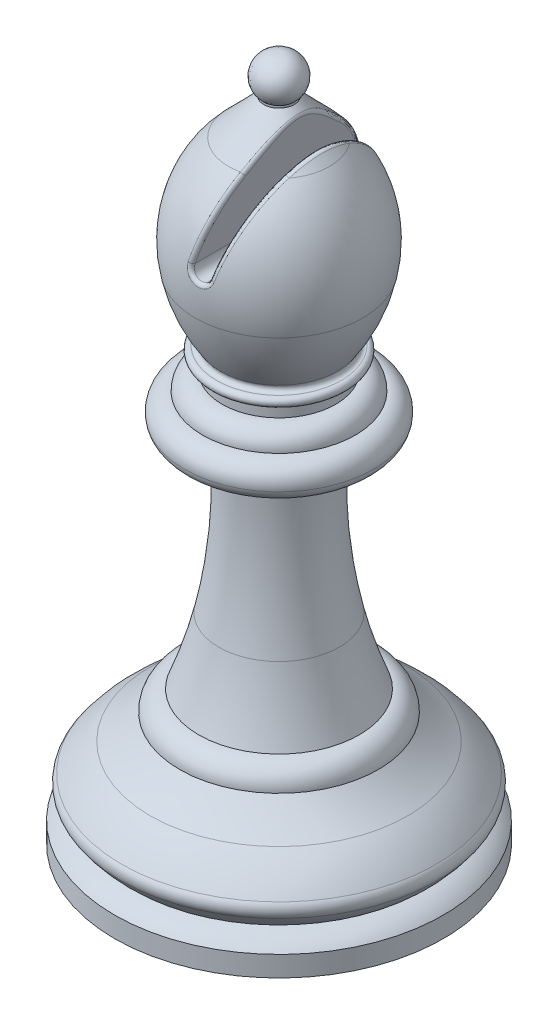
SolidWorks part; units mm, degrees
material "CA"
ref_plane "Front Plane" through (0, 0, 0) normal (0, 0, 1) x (1, 0, 0)
ref_plane "Top Plane" through (0, 0, 0) normal (0, 1, 0) x (1, 0, 0)
ref_plane "Right Plane" through (0, 0, 0) normal (1, 0, 0) x (0, 0, -1)
sketch "Sketch1" plane through (0, 0, 0) normal (0, 0, 1) x (1, 0, 0)
  line L0 (15.3, 173.706) -> (127.3, 173.706) construction
  line L1 (0, 0) -> (-11.9047, 0)
  line L2 (-11.9047, 0) -> (-11.9047, 1.4795)
  line L3 (-3.6158, 26.0106) -> (-5.794, 26.0106)
  line L4 (-4.1156, 29.6179) -> (-4.1156, 30.5678)
  line L5 (-3.6528, 44.2984) -> (-1.1, 46.9038)
  line L6 (-1.1, 46.9038) -> (-1.1, 47.0622)
  line L7 (0, 49.5976) -> (0, 0)
  arc A0 (-11.9047, 1.4795) -> (-10.4944, 2.3281) centre (-9.7951, -0.4301) cw
  arc A1 (-11.4556, 3.4168) -> (-10.4944, 2.3281) centre (-6.3809, 6.9286) ccw
  arc A2 (-11.4556, 3.4168) -> (-11.3893, 4.4063) centre (-10.8009, 3.8699) cw
  arc A3 (-11.3893, 4.4063) -> (-9.3337, 6.424) centre (-4.2404, -0.821) cw
  arc A4 (-9.3337, 6.424) -> (-7.1897, 8.2451) centre (-18.1976, 19.0323) ccw
  arc A5 (-7.1897, 8.2451) -> (-5.8113, 9.7342) centre (-5.7284, 8.275) cw
  arc A6 (-5.8113, 9.7342) -> (-4.3585, 14.505) centre (-36.4302, 21.6652) ccw
  arc A7 (-4.3585, 14.505) -> (-3.6158, 26.0106) centre (-40.757, 22.6312) ccw
  arc A8 (-5.794, 26.0106) -> (-6.8316, 26.8951) centre (-5.794, 27.0615) cw
  arc A9 (-6.8316, 26.8951) -> (-5.5288, 28.386) centre (-5.5604, 27.099) cw
  arc A10 (-5.5288, 28.386) -> (-4.1156, 29.6179) centre (-4.2879, 28.3889) cw
  arc A11 (-4.1156, 30.5678) -> (-4.61, 30.6582) centre (-3.5644, 34.9779) cw
  arc A12 (-4.61, 30.6582) -> (-4.5118, 31.3088) centre (-4.5323, 30.9792) cw
  arc A13 (-4.5118, 31.3088) -> (-4.2557, 31.7587) centre (-4.4939, 31.5964) ccw
  arc A14 (-4.2557, 31.7587) -> (-6.0674, 36.0018) centre (5.5937, 38.4723) cw
  arc A15 (-6.0674, 36.0018) -> (-3.6528, 44.2984) centre (2.8803, 37.8974) cw
  arc A16 (-1.1, 47.0622) -> (0, 49.5976) centre (-0.1457, 48.1545) cw
revolve "Revolve1" add sketch "Sketch1" angle 360 about L7
sketch "Sketch2" plane through (0, 0, 0) normal (0, 0, 1) x (1, 0, 0)
  line L0 (-0.181, 39.2523) -> (1.9721, 48.1779)
  line L1 (-0.181, 39.2523) -> (1.0583, 38.9534) construction
  line L2 (1.9721, 48.1779) -> (3.5212, 47.7171)
  line L3 (1.0583, 38.9534) -> (3.5212, 47.7171)
  arc A0 (-0.181, 39.2523) -> (1.0583, 38.9534) centre (0.4386, 39.1029) ccw
extrude "Cut-Extrude1" cut sketch "Sketch2" against normal through all both and the other way through all
fillet "Fillet1" radius 0.254
